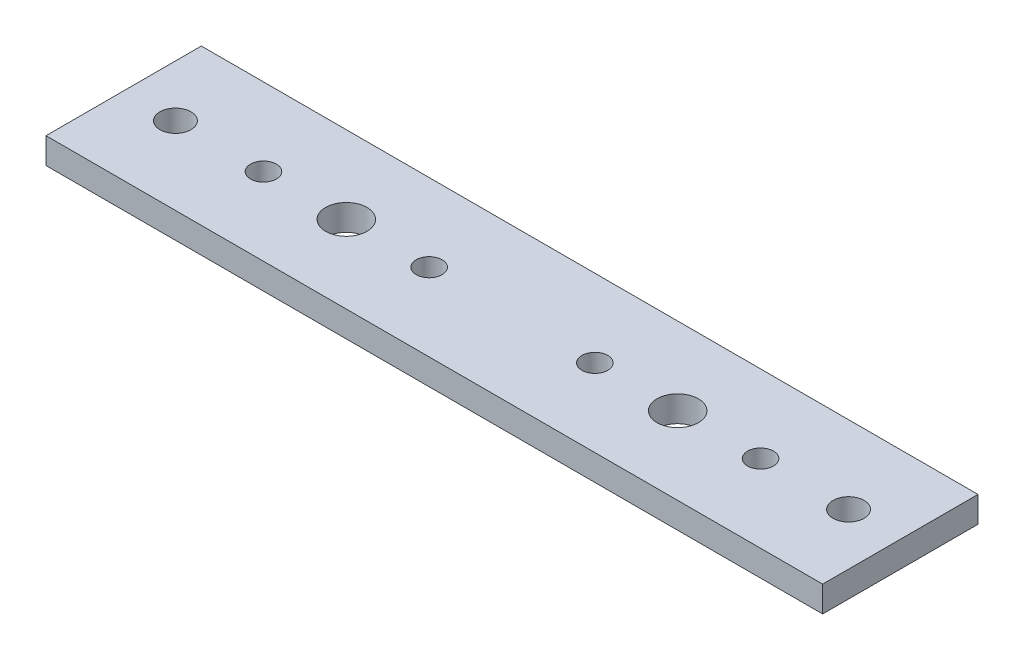
SolidWorks part; units mm, degrees
ref_plane "Front Plane" through (0, 0, 0) normal (0, 0, 1) x (1, 0, 0)
ref_plane "Top Plane" through (0, 0, 0) normal (0, 1, 0) x (1, 0, 0)
ref_plane "Right Plane" through (0, 0, 0) normal (1, 0, 0) x (0, 0, -1)
sketch "Sketch1" plane through (0, 0, 0) normal (0, 1, 0) x (1, 0, 0)
  line L0 (-93.9314, 26.2271) -> (56.0686, 26.2271) construction
  line L1 (-93.9314, 41.2271) -> (56.0686, 41.2271)
  line L2 (-93.9314, 41.2271) -> (-93.9314, 11.2271)
  line L3 (-93.9314, 11.2271) -> (56.0686, 11.2271)
  line L4 (56.0686, 41.2271) -> (56.0686, 11.2271)
  line L5 (-18.9314, 41.2271) -> (-18.9314, 11.2271) construction
  line L6 (-73.9314, 36.2271) -> (-93.9314, 36.2271) construction
  line L7 (-73.9314, 36.2271) -> (-73.9314, 16.2271) construction
  line L8 (-73.9314, 16.2271) -> (-93.9314, 16.2271) construction
  line L9 (-93.9314, 36.2271) -> (-93.9314, 16.2271) construction
  line L10 (-73.9314, 36.2271) -> (-93.9314, 16.2271) construction
  line L11 (-73.9314, 16.2271) -> (-93.9314, 36.2271) construction
  circle A0 centre (-83.9314, 26.2271) radius 3
  circle A1 centre (46.0686, 26.2271) radius 3
  circle A2 centre (-50.9314, 26.2271) radius 4
  circle A3 centre (-34.9314, 26.2271) radius 2.5
  circle A4 centre (-66.9314, 26.2271) radius 2.5
  circle A5 centre (-2.9314, 26.2271) radius 2.5
  circle A6 centre (13.0686, 26.2271) radius 4
  circle A7 centre (29.0686, 26.2271) radius 2.5
  point P6 (-83.9314, 26.2271)
  dimension "D5" = 6
  dimension "D6" = 8
  dimension "D8" = 5
  dimension "D9" = 5
  dimension "D1" = 150
  dimension "D2" = 30
  dimension "D3" = 20
  dimension "D4" = 20
  dimension "D7" = 32
  dimension "D10" = 16
  dimension "D11" = 16
extrude "Boss-Extrude1" add sketch "Sketch1" along normal blind 5
